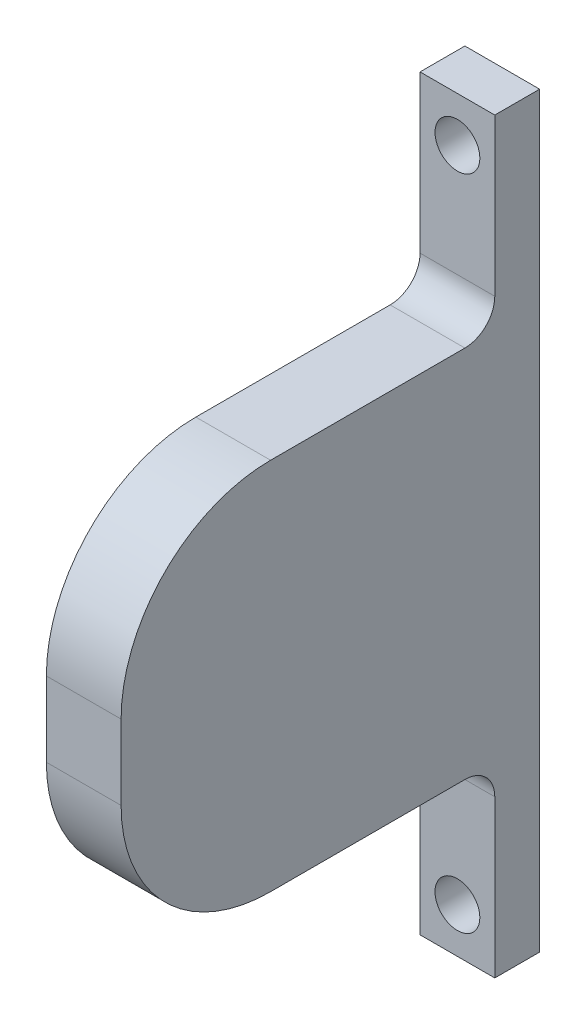
SolidWorks part; units mm, degrees
material "6063-T5"
ref_plane "前视基准面" through (0, 0, 0) normal (0, 0, 1) x (1, 0, 0)
ref_plane "上视基准面" through (0, 0, 0) normal (0, 1, 0) x (1, 0, 0)
ref_plane "右视基准面" through (0, 0, 0) normal (1, 0, 0) x (0, 0, -1)
sketch "草图1" plane through (0, 0, 0) normal (1, 0, 0) x (0, 0, -1)
  line L0 (25, 25) -> (25, 37.5)
  line L1 (0, 0) -> (25, 0)
  line L2 (0, 0) -> (0, 25)
  line L3 (0, 25) -> (25, 25)
  line L5 (25, -12.5) -> (28, -12.5)
  line L6 (25, -12.5) -> (25, 0)
  line L7 (25, 37.5) -> (28, 37.5)
  line L8 (28, -12.5) -> (28, 37.5)
  point P9 (28, 12.5)
  point P10 (0, 12.5)
  dimension "D1" = 3
  dimension "D2" = 25
  dimension "D3" = 50
  dimension "D4" = 25
extrude "凸台-拉伸2" add sketch "草图1" along normal blind 5
sketch "草图2" plane through (0, 0, -25) normal (0, 0, 1) x (1, 0, 0)
  line L0 (0, 12.5) -> (5, 12.5) construction
  line L1 (0, 25) -> (0, 0) construction
  line L2 (5, 25) -> (5, 0) construction
  line L3 (5, 37.5) -> (0, 37.5) construction
  circle A0 centre (2.5, 34.5) radius 1.5
  circle A1 centre (2.5, -9.5) radius 1.5
  point P10 (2.5, 37.5)
  dimension "D1" = 3
  dimension "D2" = 3
extrude "切除-拉伸1" cut sketch "草图2" against normal blind 4
sketch "草图3" plane through (0, 0, 0) normal (-1, 0, 0) x (0, 0, 1)
  line L0 (-28, -12.5) -> (-28, 37.5) construction
  line L1 (-28, 37.5) -> (-25, 37.5) construction
  circle A0 centre (-8, 12.5) radius 5.05
  dimension "D1" = 20
  dimension "D3" = 10.1
  dimension "D2" = 25
extrude "切除-拉伸2" cut sketch "草图3" against normal blind 3
chamfer "倒角1" distance 0.5 angle 45 1 edges at (0, 12.5, -2.95)
fillet "圆角1" radius 10 2 edges at (2.5, 0, 0) (2.5, 25, 0)
fillet "圆角2" radius 2 2 edges at (2.5, 0, -25) (2.5, 25, -25)
